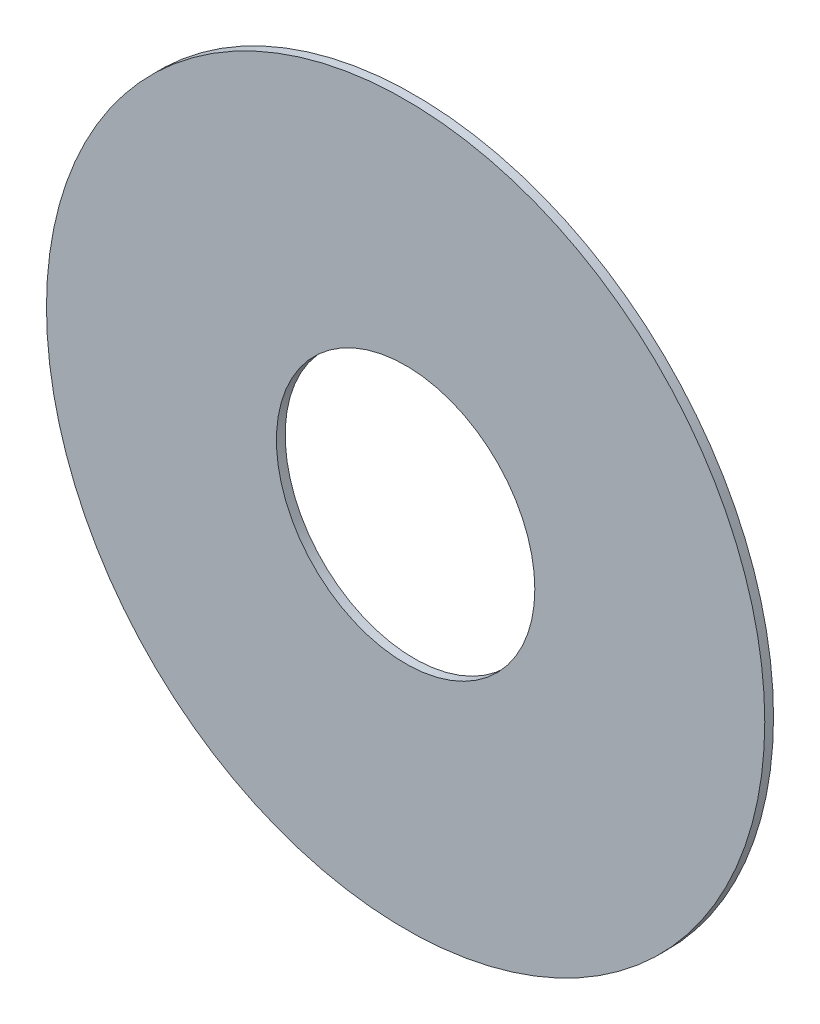
SolidWorks part; units mm, degrees
ref_plane "Спереди" through (0, 0, 0) normal (0, 0, 1) x (1, 0, 0)
ref_plane "Сверху" through (0, 0, 0) normal (0, 1, 0) x (1, 0, 0)
ref_plane "Справа" through (0, 0, 0) normal (1, 0, 0) x (0, 0, -1)
sketch "Эскиз1" plane through (0, 0, 0) normal (0, 0, 1) x (1, 0, 0)
  circle A0 centre (0, 0) radius 82
  circle A1 centre (0, 0) radius 29.5
extrude "Printed_guard" add sketch "Эскиз1" along normal blind 2 from offset 40.5
